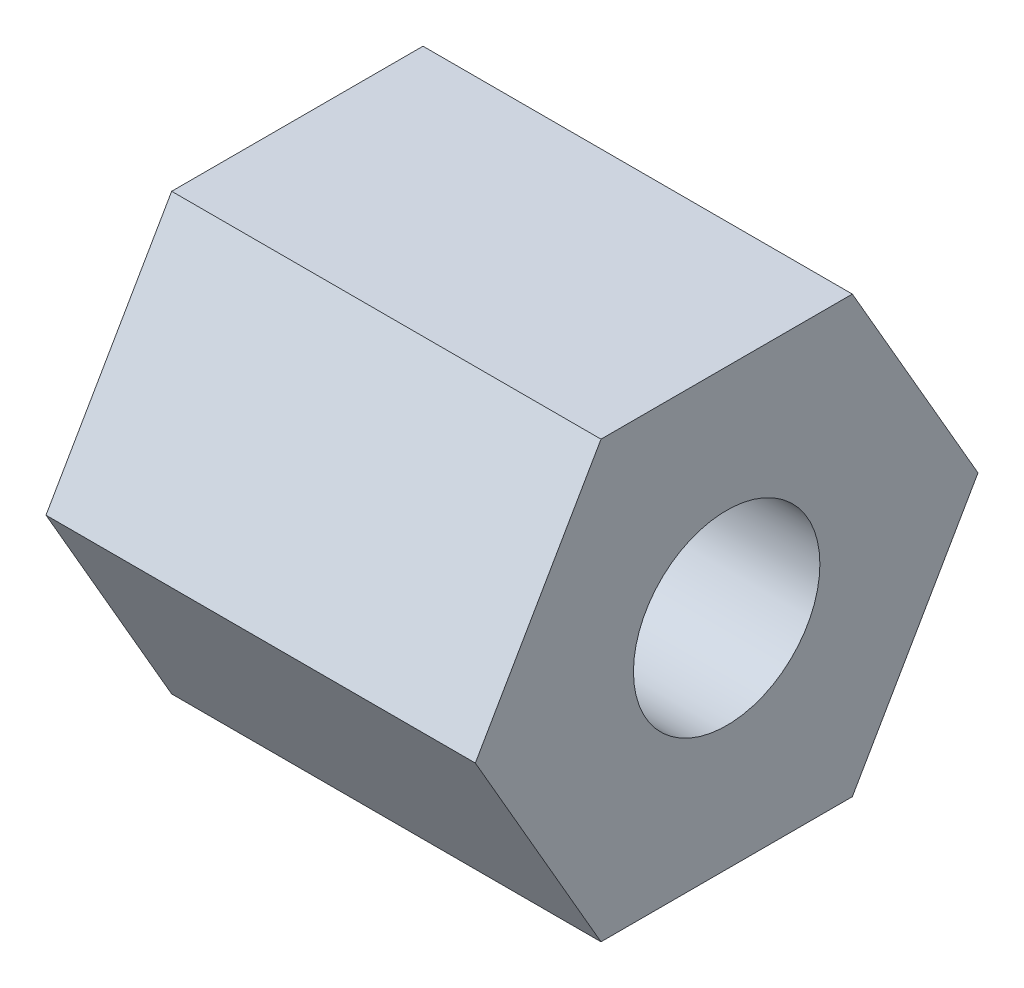
SolidWorks part; units mm, degrees
material "6061-T4 (SS)"
ref_plane "Front Plane" through (0, 0, 0) normal (0, 0, 1) x (1, 0, 0)
ref_plane "Top Plane" through (0, 0, 0) normal (0, 1, 0) x (1, 0, 0)
ref_plane "Right Plane" through (0, 0, 0) normal (1, 0, 0) x (0, 0, -1)
sketch "Sketch1" plane through (0, 0, 0) normal (1, 0, 0) x (0, 0, -1)
  line L0 (0, 0) -> (2.9445, 0) construction
  line L1 (2.9445, 0) -> (1.4722, 2.55)
  line L2 (1.4722, 2.55) -> (-1.4722, 2.55)
  line L3 (-1.4722, 2.55) -> (-2.9445, 0)
  line L4 (-2.9445, 0) -> (-1.4722, -2.55)
  line L5 (-1.4722, -2.55) -> (1.4722, -2.55)
  line L6 (1.4722, -2.55) -> (2.9445, 0)
  circle A0 centre (0, 0) radius 2.55 construction
  point P1 (-2.2084, 1.275)
  dimension "D1" = 5.1
extrude "Boss-Extrude1" add sketch "Sketch1" along normal blind 5.03
sketch "Sketch2" plane through (5.03, 0, 0) normal (1, 0, 0) x (0, 0, -1)
  circle A0 centre (0, 0) radius 1.0922
  dimension "D1" = 2.1844
extrude "Cut-Extrude1" cut sketch "Sketch2" against normal through all contours A0
